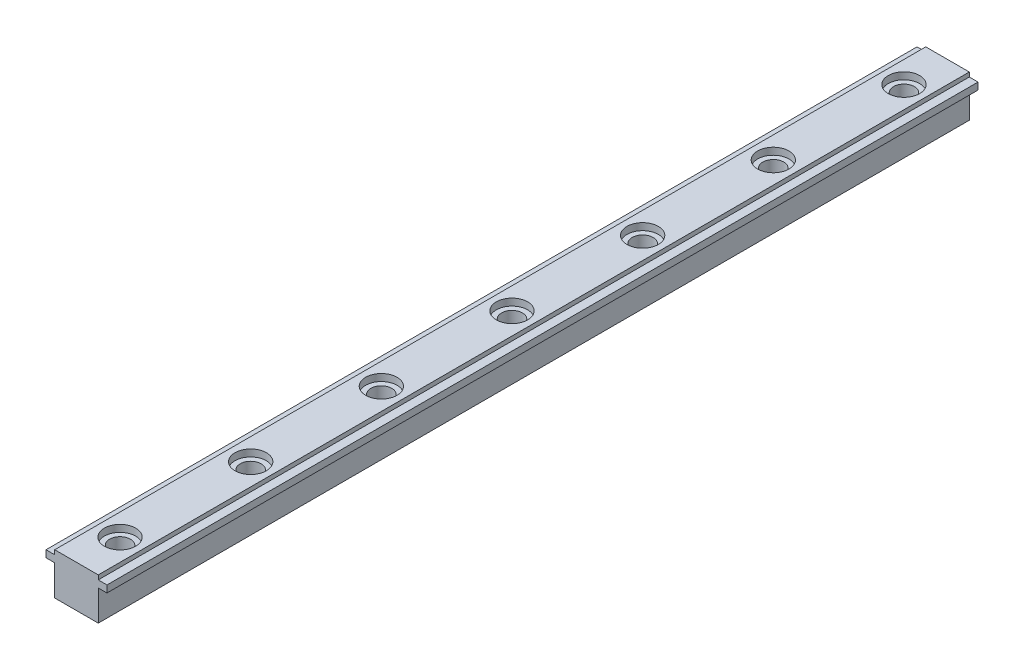
SolidWorks part; units mm, degrees
ref_plane "Front" through (0, 0, 0) normal (0, 0, 1) x (1, 0, 0)
ref_plane "Top" through (0, 0, 0) normal (0, 1, 0) x (1, 0, 0)
ref_plane "Right" through (0, 0, 0) normal (1, 0, 0) x (0, 0, -1)
sketch "草图1" plane through (0, 0, 0) normal (0, 0, 1) x (1, 0, 0)
  line L0 (2.3401, 1.468) -> (2.3401, 0.968)
  line L1 (-2.6599, 1.468) -> (2.3401, 1.468)
  line L2 (-2.6599, 1.468) -> (-2.6599, -3.332)
  line L3 (-2.6599, -3.332) -> (2.3401, -3.332)
  line L4 (2.3401, 1.468) -> (2.3401, -3.332)
  line L5 (2.3401, 0.968) -> (3.3401, 0.968)
  line L6 (3.3401, 0.968) -> (3.3401, 0.168)
  line L7 (3.3401, 0.168) -> (2.3401, 0.168)
  line L8 (-0.1599, 1.468) -> (-0.1599, -3.332) construction
  line L9 (-3.6599, 0.168) -> (-2.6599, 0.168)
  line L10 (-3.6599, 0.968) -> (-3.6599, 0.168)
  line L11 (-2.6599, 0.968) -> (-3.6599, 0.968)
  dimension "D1" = 5
  dimension "D2" = 4.8
  dimension "D3" = 0.5
  dimension "D4" = 1
  dimension "D5" = 0.8
  dimension "D6" = 2.3401
  dimension "D7" = 1.468
extrude "凸台-拉伸1" add sketch "草图1" along normal blind 40 contours L2 L11 L10 L9 | L8 L1 L2 L3 | L1 L8 L3 L4 L0 | L7 L6 L5 L4
sketch "草图2" plane through (0, 1.468, 0) normal (0, 1, 0) x (1, 0, 0)
  line L0 (-0.1599, -40) -> (-0.1599, 0) construction
  line L1 (-2.6599, -40) -> (2.3401, -40) construction
  line L2 (-2.6599, 0) -> (2.3401, 0) construction
  line L3 (-0.1599, -40) -> (-0.1599, -35) construction
  line L4 (-2.6599, -20) -> (2.3401, -20) construction
  line L5 (-2.6599, -40) -> (-2.6599, 0) construction
  line L6 (2.3401, -40) -> (2.3401, 0) construction
  circle A0 centre (-0.1599, -35) radius 1.2
  circle A1 centre (-0.1599, -20) radius 1.2
  circle A2 centre (-0.1599, -5) radius 1.2
  dimension "D2" = 2.4
  dimension "D3" = 2.4
  dimension "D1" = 5
extrude "切除-拉伸1" cut sketch "草图2" against normal blind 55 contours A2 L0 | A2 L0 | L0 A1 L4 | L0 A1 L4 | L4 A1 L0 | L4 A1 L0 | L3 A0 L0
sketch "草图3" plane through (0, 1.468, 0) normal (0, 1, 0) x (1, 0, 0)
  line L0 (-0.1599, -40) -> (-0.1599, -35)
  line L1 (-2.6599, -40) -> (2.3401, -40) construction
  circle A0 centre (-0.1599, -35) radius 1.8
  circle A1 centre (-0.1599, -20) radius 1.8
  circle A2 centre (-0.1599, -5) radius 1.8
  dimension "D1" = 3.6
  dimension "D2" = 3.6
  dimension "D3" = 3.6
extrude "切除-拉伸2" cut sketch "草图3" against normal blind 0.8
other "移动面2" face at (-0.1599, 0.068, 40) parameters "D1"=60
pattern_linear "阵列(线性)1" count 5 spacing 15 along (0, 0, 1) of "切除-拉伸1", "切除-拉伸2"
